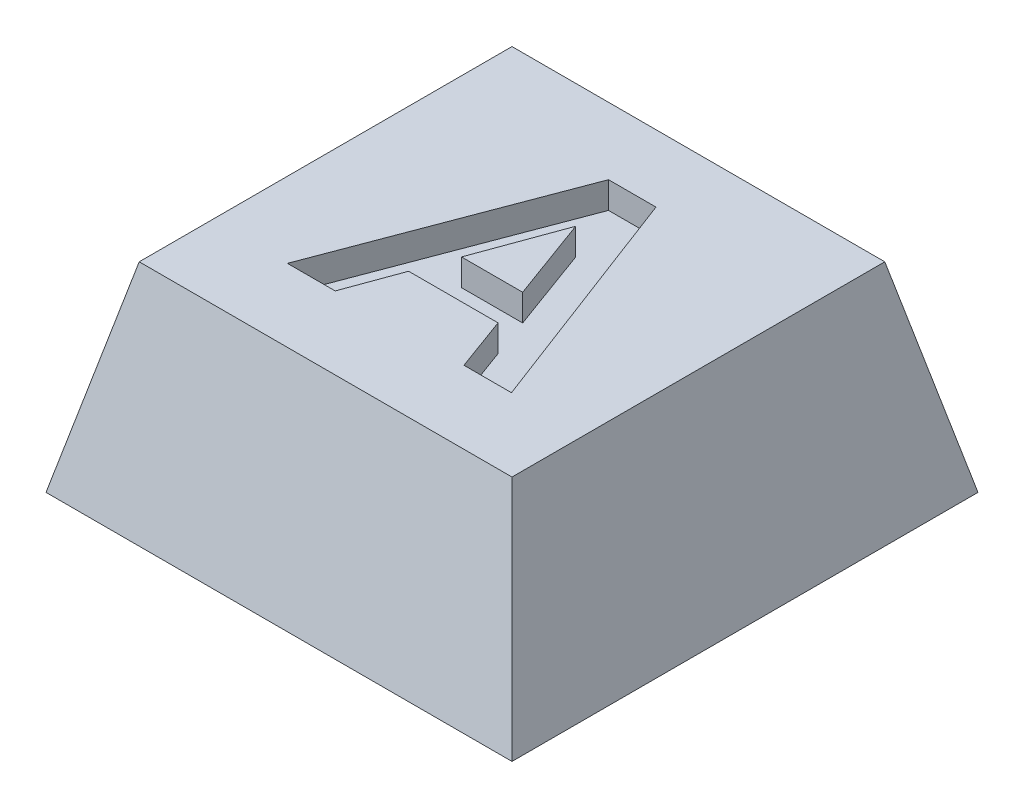
SolidWorks part; units mm, degrees
ref_plane "Front Plane" through (0, 0, 0) normal (0, 0, 1) x (1, 0, 0)
ref_plane "Top Plane" through (0, 0, 0) normal (0, 1, 0) x (1, 0, 0)
ref_plane "Right Plane" through (0, 0, 0) normal (1, 0, 0) x (0, 0, -1)
sketch "Sketch1" plane through (0, 0, 0) normal (0, 1, 0) x (1, 0, 0)
  line L1 (0, 0) -> (7, 0)
  line L2 (0, 0) -> (0, 7)
  line L3 (0, 7) -> (7, 7)
  line L4 (7, 0) -> (7, 7)
  dimension "D1" = 7
  dimension "D2" = 7
extrude "Boss-Extrude1" add sketch "Sketch1" along normal blind 3
sketch "Sketch2" plane through (0, 0, 0) normal (0, 0, 1) x (1, 0, 0)
  line L0 (0, 0) -> (0.7, 3)
  line L1 (0, 3) -> (7, 3) construction
  line L2 (0.7, 3) -> (0, 3)
  line L3 (0, 3) -> (0, 0)
  line L4 (7, 0) -> (6.3, 3)
  line L5 (6.3, 3) -> (7, 3)
  line L6 (7, 3) -> (7, 0)
  dimension "D1" = 0.7
  dimension "D2" = 0.7
extrude "Cut-Extrude1" cut sketch "Sketch2" against normal blind 7
sketch "Sketch3" plane through (0, 0, 0) normal (1, 0, 0) x (0, 0, -1)
  line L0 (0, 0) -> (0.7, 3)
  line L1 (7, 3) -> (0, 3) construction
  line L2 (0.7, 3) -> (0, 3)
  line L3 (0, 3) -> (0, 0)
  line L4 (7, 3) -> (6.3, 3)
  line L5 (6.3, 3) -> (7, 0)
  line L6 (7, 3) -> (7, 0)
  dimension "D1" = 0.7
  dimension "D2" = 0.7
extrude "Cut-Extrude2" cut sketch "Sketch3" along normal blind 11
sketch "Sketch4" plane through (0, 0, 0) normal (0, -1, 0) x (1, 0, 0)
  line L0 (3.5, 0) -> (3.5, -7) construction
  line L1 (0, 0) -> (7, 0) construction
  line L2 (7, -7) -> (0, -7) construction
  line L3 (0, -3.5) -> (7, -3.5) construction
  line L4 (0, -7) -> (0, 0) construction
  line L5 (7, 0) -> (7, -7) construction
  circle A0 centre (3.5, -3.5) radius 1.8
  dimension "D1" = 3.6
extrude "Cut-Extrude3" cut sketch "Sketch4" against normal blind 0.8
sketch "Sketch5" plane through (0, 3, 0) normal (0, 1, 0) x (1, 0, 0)
  text T0 "A" font "Arial" height 3.5
extrude "Cut-Extrude4" cut sketch "Sketch5" against normal blind 0.4
